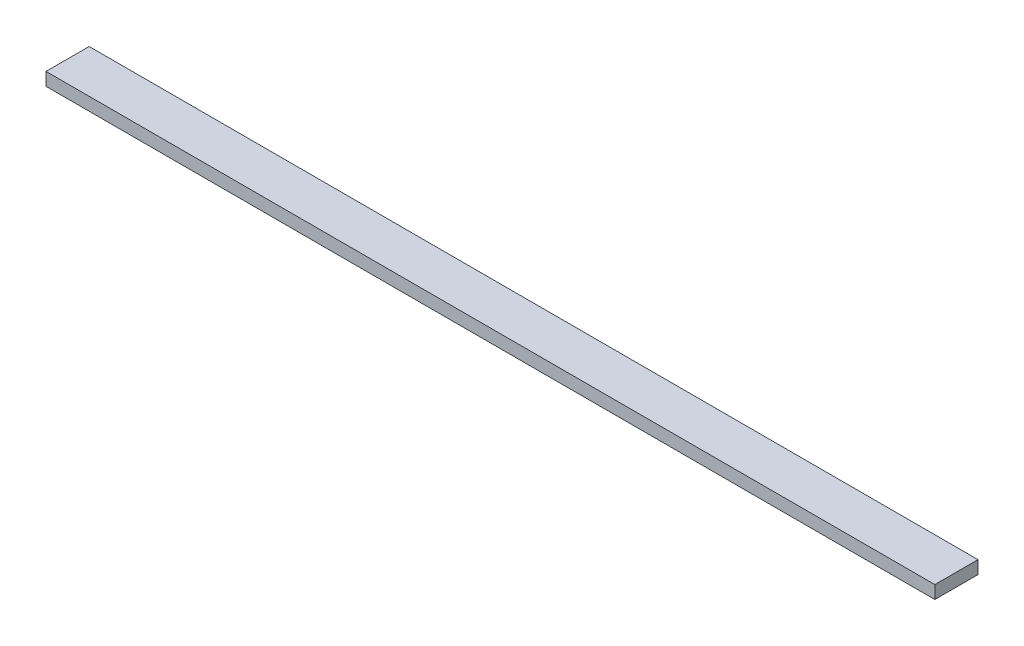
SolidWorks part; units mm, degrees
ref_plane "Front Plane" through (0, 0, 0) normal (0, 0, 1) x (1, 0, 0)
ref_plane "Top Plane" through (0, 0, 0) normal (0, 1, 0) x (1, 0, 0)
ref_plane "Right Plane" through (0, 0, 0) normal (1, 0, 0) x (0, 0, -1)
sketch "Sketch1" plane through (0, 0, 0) normal (0, 1, 0) x (1, 0, 0)
  line L1 (-103, -5) -> (103, -5)
  line L2 (-103, -5) -> (-103, 5)
  line L3 (-103, 5) -> (103, 5)
  line L4 (103, -5) -> (103, 5)
  line L5 (-103, -5) -> (103, 5) construction
  line L6 (-103, 5) -> (103, -5) construction
  point P0 (0, 0)
  dimension "D1" = 10
  dimension "D2" = 206
extrude "Boss-Extrude1" add sketch "Sketch1" along normal mid plane 3
